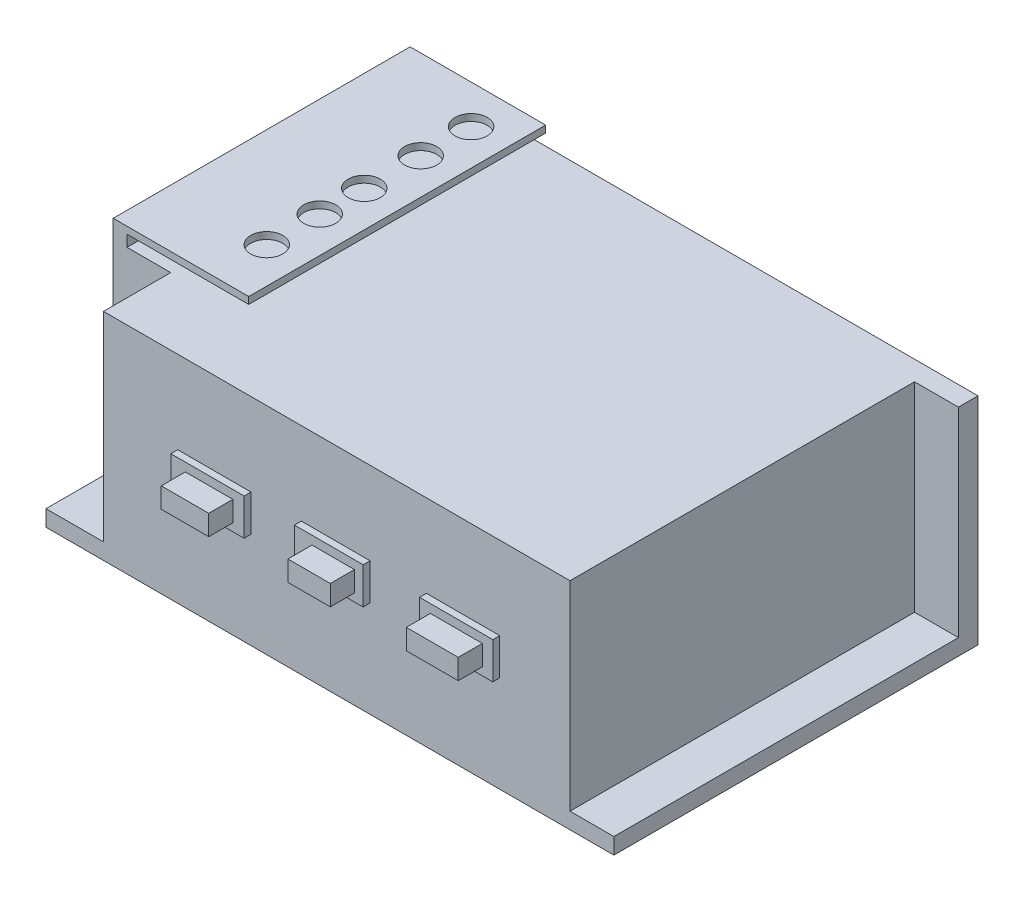
SolidWorks part; units mm, degrees
ref_plane "前视基准面" through (0, 0, 0) normal (0, 0, 1) x (1, 0, 0)
ref_plane "上视基准面" through (0, 0, 0) normal (0, 1, 0) x (1, 0, 0)
ref_plane "右视基准面" through (0, 0, 0) normal (1, 0, 0) x (0, 0, -1)
sketch "草图1" plane through (0, 0, 0) normal (0, 0, 1) x (1, 0, 0)
  line L1 (-82.5, -34) -> (82.5, -34)
  line L2 (-82.5, -34) -> (-82.5, 34)
  line L3 (-82.5, 34) -> (82.5, 34)
  line L4 (82.5, -34) -> (82.5, 34)
  line L5 (-82.5, -34) -> (82.5, 34) construction
  line L6 (-82.5, 34) -> (82.5, -34) construction
  point P0 (0, 0)
  dimension "D1" = 68
  dimension "D2" = 165
extrude "凸台-拉伸1" add sketch "草图1" along normal blind 105.8
sketch "草图2" plane through (0, 34, 0) normal (0, 1, 0) x (1, 0, 0)
  line L1 (-43.1184, 12.1433) -> (99.7812, 12.1433)
  line L2 (-43.1184, 12.1433) -> (-43.1184, -111.3717)
  line L3 (-43.1184, -111.3717) -> (99.7812, -111.3717)
  line L4 (99.7812, 12.1433) -> (99.7812, -111.3717)
  line L5 (-99.7812, -86.2711) -> (-22.9882, -86.2711)
  line L6 (-99.7812, -86.2711) -> (-99.7812, -111.3717)
  line L7 (-99.7812, -111.3717) -> (-22.9882, -111.3717)
  line L8 (-22.9882, -86.2711) -> (-22.9882, -111.3717)
  line M1 (82.5, 0) -> (-82.5, 0)
  line M2 (-82.5, 0) -> (-82.5, -105.8)
  line M3 (-82.5, -105.8) -> (82.5, -105.8)
  line M4 (82.5, -105.8) -> (82.5, 0)
extrude "切除-拉伸1" cut sketch "草图2" against normal blind 2 contours L5 L2 M2 M3 | L8 L5 L2 M3 | L5 L8 L2 M3 M4 M1
sketch "草图3" plane through (0, 34, 0) normal (0, 1, 0) x (1, 0, 0)
  circle A0 centre (-53.5563, -11.2177) radius 4.6693
  circle A1 centre (-53.5563, -25.8805) radius 4.6693
  circle A2 centre (-53.5563, -42.2828) radius 4.6693
  circle A3 centre (-53.5563, -55.2059) radius 4.6693
  circle A4 centre (-53.5563, -70.6142) radius 4.6693
extrude "切除-拉伸2" cut sketch "草图3" against normal blind 2
sketch "草图4" plane through (0, 0, 105.8) normal (0, 0, 1) x (1, 0, 0)
  line L1 (-44.2246, 4.6552) -> (-22.9436, 4.6552)
  line L2 (-44.2246, 4.6552) -> (-44.2246, -5.9853)
  line L3 (-44.2246, -5.9853) -> (-22.9436, -5.9853)
  line L4 (-22.9436, 4.6552) -> (-22.9436, -5.9853)
  line L5 (-8.3129, 4.6552) -> (11.638, 4.6552)
  line L6 (-8.3129, 4.6552) -> (-8.3129, -5.9853)
  line L7 (-8.3129, -5.9853) -> (11.638, -5.9853)
  line L8 (11.638, 4.6552) -> (11.638, -5.9853)
  line L9 (28.0421, 4.6552) -> (49.3231, 4.6552)
  line L10 (28.0421, 4.6552) -> (28.0421, -5.9853)
  line L11 (28.0421, -5.9853) -> (49.3231, -5.9853)
  line L12 (49.3231, 4.6552) -> (49.3231, -5.9853)
extrude "凸台-拉伸2" add sketch "草图4" along normal blind 2
sketch "草图5" plane through (0, 0, 107.8) normal (0, 0, 1) x (1, 0, 0)
  line L1 (-40.0153, 2.1717) -> (-26.2159, 2.1717)
  line L2 (-40.0153, 2.1717) -> (-40.0153, -3.7161)
  line L3 (-40.0153, -3.7161) -> (-26.2159, -3.7161)
  line L4 (-26.2159, 2.1717) -> (-26.2159, -3.7161)
  line L5 (-3.2169, 2.1717) -> (9.1105, 2.1717)
  line L6 (-3.2169, 2.1717) -> (-3.2169, -3.7161)
  line L7 (-3.2169, -3.7161) -> (9.1105, -3.7161)
  line L8 (9.1105, 2.1717) -> (9.1105, -3.7161)
  line L9 (31.1896, 2.1717) -> (46.2769, 2.1717)
  line L10 (31.1896, 2.1717) -> (31.1896, -3.7161)
  line L11 (31.1896, -3.7161) -> (46.2769, -3.7161)
  line L12 (46.2769, 2.1717) -> (46.2769, -3.7161)
extrude "凸台-拉伸3" add sketch "草图5" along normal blind 7
sketch "草图6" plane through (82.5, 0, 0) normal (1, 0, 0) x (0, 0, -1)
  line L0 (0, -34) -> (0, 32) construction
  line L1 (-105.8, 32) -> (0, 32)
  line L2 (-105.8, 32) -> (-105.8, 28.6874)
  line L3 (-105.8, 28.6874) -> (0, 28.6874)
  line L4 (0, 32) -> (0, 28.6874)
extrude "切除-拉伸3" cut sketch "草图6" against normal blind 161
sketch "草图7" plane through (0, 28.6874, 0) normal (0, 1, 0) x (1, 0, 0)
  line L0 (-78.5, -105.8) -> (82.5, -105.8) construction
  line L1 (-82.5, -86.2711) -> (-65.7897, -86.2711)
  line L2 (-82.5, -86.2711) -> (-82.5, -105.8)
  line L3 (-82.5, -105.8) -> (-65.7897, -105.8)
  line L4 (-65.7897, -86.2711) -> (-65.7897, -105.8)
extrude "切除-拉伸4" cut sketch "草图7" against normal blind 58 and the other way blind 58
sketch "草图8" plane through (0, 28.6874, 0) normal (0, 1, 0) x (1, 0, 0)
  line L1 (69.7485, -5.6872) -> (89.859, -5.6872)
  line L2 (69.7485, -5.6872) -> (69.7485, -110.7089)
  line L3 (69.7485, -110.7089) -> (89.859, -110.7089)
  line L4 (89.859, -5.6872) -> (89.859, -110.7089)
extrude "切除-拉伸5" cut sketch "草图8" against normal up to surface (58 mm away) up to face at (-74.1448, -29.3126, 96.0355)
